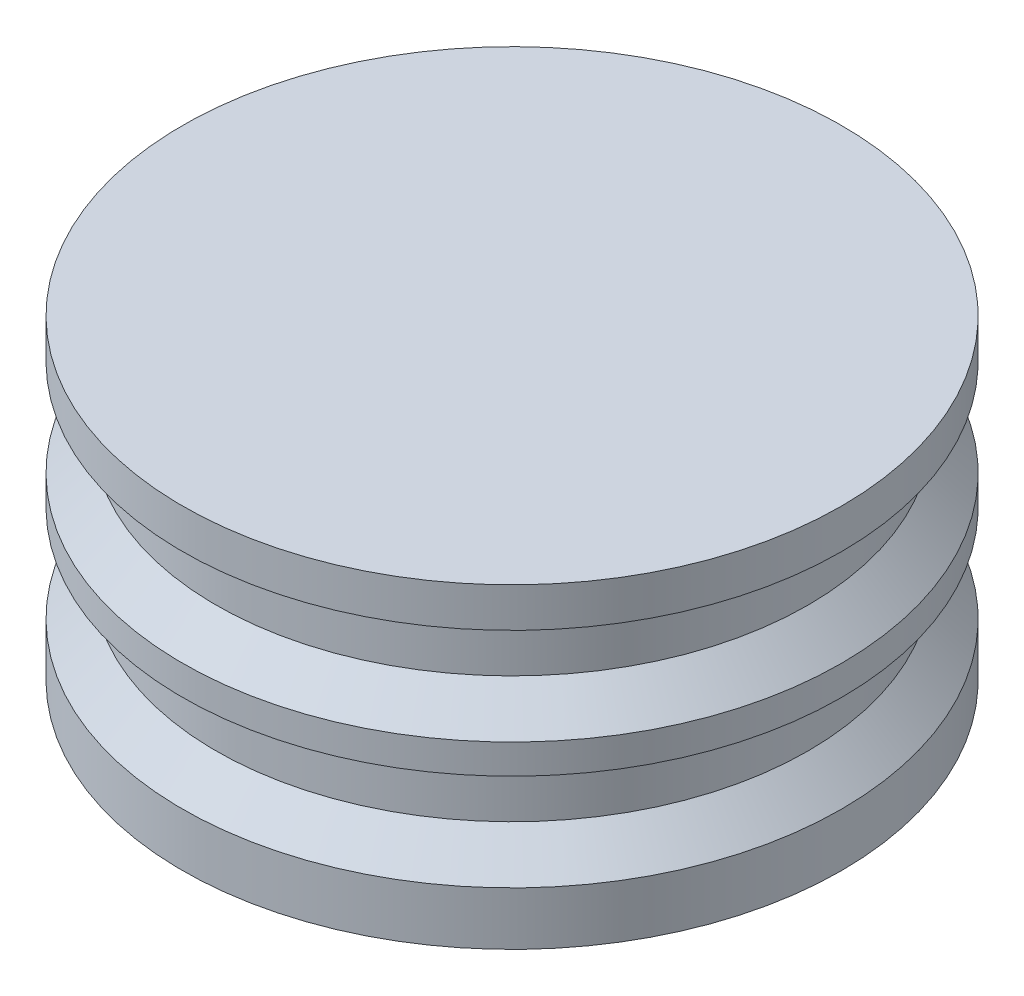
SolidWorks part; units mm, degrees
material "3D printed plastic"
ref_plane "Front Plane" through (0, 0, 0) normal (0, 0, 1) x (1, 0, 0)
ref_plane "Top Plane" through (0, 0, 0) normal (0, 1, 0) x (1, 0, 0)
ref_plane "Right Plane" through (0, 0, 0) normal (1, 0, 0) x (0, 0, -1)
sketch "Sketch1" plane through (0, 0, 0) normal (0, 0, 1) x (1, 0, 0)
  line L0 (0, 0) -> (-41.75, 0)
  line L1 (-41.75, 0) -> (-41.75, -5)
  line L2 (-41.75, -5) -> (-37.5, -5)
  line L3 (-37.5, -5) -> (-37.5, -13)
  line L4 (-37.5, -13) -> (-41.75, -17.25)
  line L5 (-41.75, -17.25) -> (-41.75, -21)
  line L6 (-41.75, -40) -> (0, -40)
  line L7 (0, -40) -> (0, 0) construction
  line L8 (0, 0) -> (0, -40)
  line L9 (-41.75, -21) -> (-37.5, -21)
  line L10 (-37.5, -21) -> (-37.5, -29)
  line L11 (-37.5, -29) -> (-41.75, -33.25)
  line L12 (-41.75, -33.25) -> (-41.75, -40)
  dimension "D1" = 83.5
  dimension "D2" = 5
  dimension "D3" = 8
  dimension "D4" = 45
  dimension "D5" = 75
  dimension "D6" = 40
  dimension "D7" = 16
revolve "Revolve1" add sketch "Sketch1" angle 360 about L7
sketch "Sketch2" plane through (0, -40, 0) normal (0, 1, 0) x (1, 0, 0)
  line L0 (-21.5, 21.5) -> (21.5, -21.5) construction
  line L1 (-21.5, 21.5) -> (-5, 21.5)
  line L2 (-21.5, 21.5) -> (-21.5, -21.5)
  line L3 (-21.5, -21.5) -> (21.5, -21.5)
  line L4 (21.5, 21.5) -> (21.5, -21.5)
  line L5 (5, 21.5) -> (21.5, 21.5)
  line L7 (-5, 21.5) -> (-5, 26.5)
  line L8 (-5, 26.5) -> (5, 26.5)
  line L9 (5, 21.5) -> (5, 26.5)
  dimension "D1" = 43
  dimension "D2" = 10
  dimension "D3" = 5
extrude "Cut-Extrude1" cut sketch "Sketch2" along normal blind 37
sketch "Sketch3" plane through (0, -40, 0) normal (0, -1, 0) x (1, 0, 0)
  line L0 (27.5, 0) -> (-27.5, 0) construction
  circle A0 centre (-27.5, 0) radius 4
  circle A1 centre (27.5, 0) radius 4
  dimension "D1" = 8
  dimension "D2" = 55
extrude "Cut-Extrude2" cut sketch "Sketch3" against normal up to surface (37 mm away) up to face at (0, -3, -12)
sketch "Sketch4" plane through (0, -40, 0) normal (0, -1, 0) x (1, 0, 0)
  line L0 (0, 0.5) -> (0, -0.5) construction
  line L1 (-36, 0.5) -> (36, 0.5)
  line L2 (-36, 0.5) -> (-36, -0.5)
  line L3 (-36, -0.5) -> (36, -0.5)
  line L4 (36, 0.5) -> (36, -0.5)
  dimension "D1" = 1
  dimension "D2" = 72
extrude "Cut-Extrude3" cut sketch "Sketch4" against normal up to surface (37 mm away) up to face at (-27.5, -3, 4)
hole_wizard "M4 Clearance Hole1" positions "Sketch6" profile "Sketch5" hole size "M4" standard "DIN"
sketch "Sketch6" plane through (0, -40, 0) normal (0, -1, 0) x (-1, 0, 0)
  line L0 (27.5, -15.5) -> (27.5, 15.5) construction
  line L1 (27.5, 15.5) -> (-27.5, 15.5) construction
  line L2 (-27.5, 15.5) -> (-27.5, -15.5) construction
  line L3 (-27.5, -15.5) -> (27.5, -15.5) construction
  line L4 (27.5, -15.5) -> (-27.5, 15.5) construction
  point P0 (27.5, -15.5)
  point P2 (-27.5, -15.5)
  point P4 (-27.5, 15.5)
  point P6 (27.5, 15.5)
  dimension "D1" = 31
  dimension "D2" = 55
sketch "Sketch5" plane through (-27.5, -40, 15.5) normal (1, 0, 0) x (0, 0, -1)
  line L0 (0, 0) -> (0, 19.3519)
  line L1 (0, 19.3519) -> (2.25, 18)
  line L2 (2.25, 18) -> (2.25, 0)
  line L5 (2.25, 0) -> (0, 0)
  line L10 (0, 19.3519) -> (-2.25, 18) construction
  line L11 (0, -6.35) -> (0, 107.95) construction
  dimension "Hole Dia." = 4.5
  dimension "Hole Depth" = 18
  dimension "Drill Angle" = 118
sketch "Sketch7" plane through (0, -40, 0) normal (0, -1, 0) x (1, 0, 0)
  line L0 (-25.4504, 19.05) -> (25.4504, 19.05)
  line L1 (-23.4008, 15.5) -> (-25.4504, 19.05) construction
  line L2 (-25.4504, 19.05) -> (-29.5496, 19.05)
  line L3 (-29.5496, 19.05) -> (-31.5992, 15.5)
  line L4 (-31.5992, 15.5) -> (-29.5496, 11.95)
  line L5 (-29.5496, 11.95) -> (-25.4504, 11.95)
  line L6 (-25.4504, 11.95) -> (-23.4008, 15.5) construction
  line L7 (23.4008, 15.5) -> (25.4504, 11.95) construction
  line L8 (25.4504, 11.95) -> (29.5496, 11.95)
  line L9 (29.5496, 11.95) -> (31.5992, 15.5)
  line L10 (31.5992, 15.5) -> (29.5496, 19.05)
  line L11 (29.5496, 19.05) -> (25.4504, 19.05)
  line L12 (25.4504, 19.05) -> (23.4008, 15.5) construction
  line L13 (25.4504, 11.95) -> (-25.4504, 11.95)
  line L14 (0, 0) -> (10.1418, 0) construction
  line L15 (25.4504, -19.05) -> (23.4008, -15.5) construction
  line L16 (23.4008, -15.5) -> (25.4504, -11.95) construction
  line L17 (-25.4504, -11.95) -> (-23.4008, -15.5) construction
  line L18 (-23.4008, -15.5) -> (-25.4504, -19.05) construction
  line L19 (25.4504, -11.95) -> (-25.4504, -11.95)
  line L20 (29.5496, -19.05) -> (25.4504, -19.05)
  line L21 (31.5992, -15.5) -> (29.5496, -19.05)
  line L22 (29.5496, -11.95) -> (31.5992, -15.5)
  line L23 (25.4504, -11.95) -> (29.5496, -11.95)
  line L24 (-29.5496, -11.95) -> (-25.4504, -11.95)
  line L25 (-31.5992, -15.5) -> (-29.5496, -11.95)
  line L26 (-29.5496, -19.05) -> (-31.5992, -15.5)
  line L27 (-25.4504, -19.05) -> (-29.5496, -19.05)
  line L28 (-25.4504, -19.05) -> (25.4504, -19.05)
  circle A0 centre (-27.5, 15.5) radius 3.55 construction
  circle A1 centre (27.5, 15.5) radius 3.55 construction
  circle A2 centre (27.5, -15.5) radius 3.55 construction
  circle A3 centre (-27.5, -15.5) radius 3.55 construction
  dimension "D1" = 7.1
extrude "Cut-Extrude4" cut sketch "Sketch7" against normal blind 6 from offset 6 offset against normal yes
sketch "Sketch8" plane through (0, -34, 0) normal (0, 1, 0) x (1, 0, 0)
  circle A0 centre (-27.5, -15.5) radius 2.25
  circle A1 centre (-27.5, 15.5) radius 2.25
  circle A2 centre (27.5, 15.5) radius 2.25
  circle A3 centre (27.5, -15.5) radius 2.25
  circle A4 centre (-27.5, -15.5) radius 2.25 construction
extrude "Boss-Extrude1" add sketch "Sketch8" against normal blind 0.5
